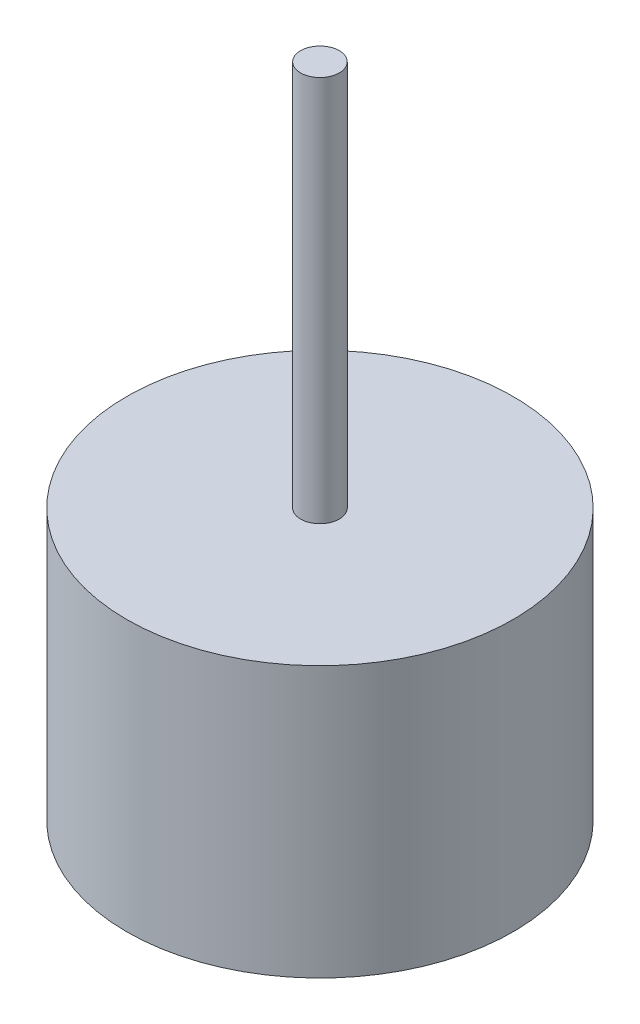
SolidWorks part; units mm, degrees
ref_plane "Plan de face" through (0, 0, 0) normal (0, 0, 1) x (1, 0, 0)
ref_plane "Plan de dessus" through (0, 0, 0) normal (0, 1, 0) x (1, 0, 0)
ref_plane "Plan de droite" through (0, 0, 0) normal (1, 0, 0) x (0, 0, -1)
sketch "Sketch1" plane through (0, 0, 0) normal (0, 1, 0) x (1, 0, 0)
  circle A0 centre (0, 0) radius 5
extrude "Boss-Extrude1" add sketch "Sketch1" along normal blind 7
sketch "Sketch2" plane through (0, 7, 0) normal (0, 1, 0) x (-1, 0, 0)
  circle A0 centre (0, 0) radius 0.5
extrude "Boss-Extrude2" add sketch "Sketch2" along normal blind 10
